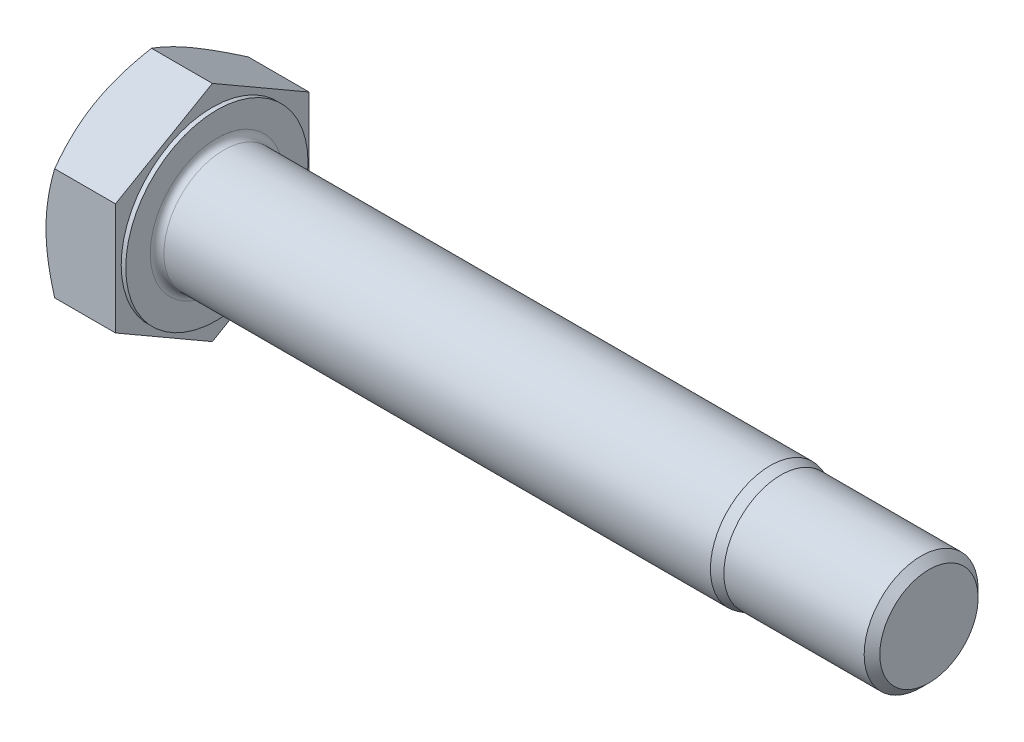
SolidWorks part; units mm, degrees
extrude "BaseHead" add sketch "HeadSke" along normal blind 13
sketch "HeadSke" plane through (0, 0, 0) normal (1, 0, 0) x (0, 0, -1)
  line L0 (17, 9.815) -> (17, -9.815)
  line L1 (-17, 9.815) -> (-17, -9.815)
  line L2 (17, -9.815) -> (0, -19.6299)
  line L3 (0, -19.6299) -> (-17, -9.815)
  line L4 (17, 9.815) -> (0, 19.6299)
  line L5 (0, 19.6299) -> (-17, 9.815)
  line L6 (0, 19.6299) -> (0, -19.6299) construction
  dimension "Width_flats" = 34
  dimension "D2" = 120
ref_plane "Plane1" through (0, 0, 0) normal (0, 0, 1) x (1, 0, 0)
ref_plane "Plane2" through (0, 0, 0) normal (0, 1, 0) x (1, 0, 0)
ref_plane "Plane3" through (0, 0, 0) normal (1, 0, 0) x (0, 0, -1)
sketch "BodySke" plane through (0, 0, 0) normal (0, 0, 1) x (1, 0, 0)
  line L0 (0, 10.5) -> (0, 0)
  line L2 (0, 0) -> (138, 0)
  line L4 (138, 0) -> (138, 8.626)
  line L5 (13, 19.6299) -> (13, 9.815) construction
  line L6 (138, 8.626) -> (136.626, 10)
  line L7 (0, 0) -> (194.2747, 0) construction
  line L8 (138, -8.626) -> (136.626, -10) construction
  line L9 (0, -10) -> (136.626, -10) construction
  line L10 (15.5, 15.24) -> (15.5, -1.27) construction
  line L11 (112, 10) -> (110.134, 10.5)
  line L12 (13, 9.815) -> (13, -9.815) construction
  line L13 (110.134, 10.5) -> (0, 10.5)
  line L15 (112, 10) -> (136.626, 10)
  dimension "D1" = 75
  dimension "Diameter" = 20
  dimension "Thread_nom" = 26
  dimension "Body_ch_ang" = 45
revolve "BaseBody" add sketch "BodySke" angle 360 about L7
cosmetic thread "ThreadCosmetic" [suppressed] parameters "Thread_length"=23.5, "Thread_minor"=17.252
sketch "Sketch3" plane through (0, 0, 0) normal (0, 1, 0) x (1, 0, 0)
  line L0 (4.25, 24.3612) -> (-4.25, 9.6388)
  line L1 (4.25, 24.3612) -> (-2.924, 28.5031)
  line L2 (-4.25, 9.6388) -> (-11.424, 13.7807)
  line L3 (-2.924, 28.5031) -> (-11.424, 13.7807)
  line L4 (0, 17) -> (0, 0) construction
  line L6 (0, 0) -> (99.06, 0) construction
  dimension "Head_ch_ang" = 30
revolve "HeadChamfer" cut sketch "Sketch3" angle 360 about L6
sketch "Sketch4" plane through (0, 0, 0) normal (0, 0, 1) x (1, 0, 0)
  line L0 (13, 19.6299) -> (1.5184, 19.6299) construction
  line L1 (13, 19.6299) -> (13, 9.815) construction
  line L2 (13, 16) -> (12.2, 16)
  line L3 (13, 16) -> (13, 19.6299)
  line L4 (13, 19.6299) -> (12.2, 19.6299)
  line L5 (0, 0) -> (95.25, 0) construction
  line L6 (0, 0) -> (194.2747, 0) construction
  line L7 (12.2, 16) -> (12.2, 19.6299)
  dimension "Bearing_ht" = 0.8
  dimension "Bearing_dia" = 32
revolve "BearingFace" cut sketch "Sketch4" angle 360 about L5
fillet "HeadFillet" radius 1.2 1 edges at (13, 0, -10.5)
sketch "ThdSchSke" plane through (0, 0, 0) normal (0, 0, 1) x (1, 0, 0)
  line L0 (114.5, -8.626) -> (113.5379, -10)
  line L1 (114.5, -8.626) -> (115.4621, -10)
  line L2 (115.4621, -10) -> (115.4621, -12.5)
  line L3 (-3.175, 0) -> (5.1513, 0) construction
  line L5 (115.4621, -12.5) -> (113.5379, -12.5)
  line L6 (113.5379, -12.5) -> (113.5379, -10)
  dimension "Thread_minor" = 17.252
  dimension "Diameter" = 20
  dimension "Start" = 114.5
revolve "ThreadSchematic" [suppressed] cut sketch "ThdSchSke" angle 360 about L3
pattern_linear "ThdSchPat" [suppressed]
equation "\"Thread_minor@ThreadCosmetic\" = \"Minor_dia@BodySke\""
equation "\"Thread_length@ThreadCosmetic\" = \"Thread_nom@BodySke\" - \"Advance@BodySke\""
equation "\"Thread_minor@ThdSchSke\" = \"Minor_dia@BodySke\""
equation "\"Diameter@ThdSchSke\" = \"Diameter@BodySke\""
equation "\"Overcut@ThdSchSke\" = \"Diameter@BodySke\" * 1.25"
equation "\"Start@ThdSchSke\" = \"Head_ht@BaseHead\" + \"Length@BodySke\" - \"Thread_length@ThreadCosmetic\"  '---Non-countersunk---"
equation "\"Num_threads@ThdSchPat\" = int( \"Thread_length@ThreadCosmetic\" / \"Advance@BodySke\" + 0.999 )  + 1"
equation "\"Advance@ThdSchPat\" = \"Thread_length@ThreadCosmetic\" /  (\"Num_threads@ThdSchPat\" - 1) 'relax it"
equation "\"Num_threads@ThdSchPat\" = \"Num_threads@ThdSchPat\" - sgn( \"Num_threads@ThdSchPat\" - 1) '---chamfered tips only---"
